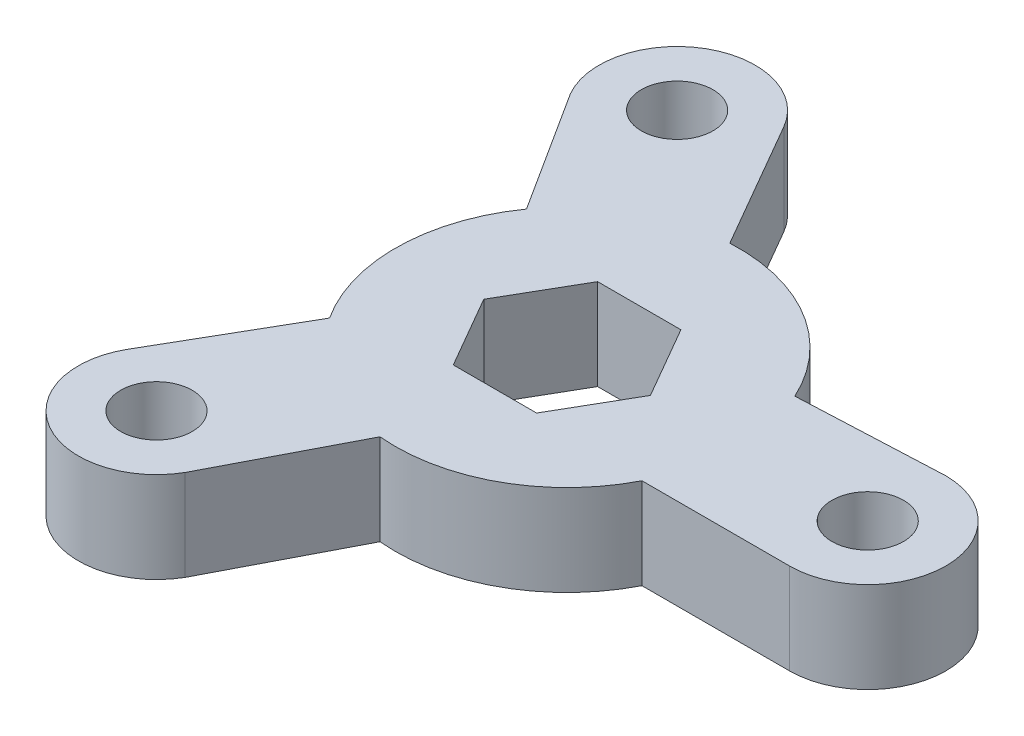
SolidWorks part; units mm, degrees
ref_plane "Front" through (0, 0, 0) normal (0, 0, 1) x (1, 0, 0)
ref_plane "Top" through (0, 0, 0) normal (0, 1, 0) x (1, 0, 0)
ref_plane "Right" through (0, 0, 0) normal (1, 0, 0) x (0, 0, -1)
sketch "Sketch1" plane through (0, 0, 0) normal (0, 1, 0) x (1, 0, 0)
  line L0 (2.5148, 0.2447) -> (13.0148, 0.2447)
  line L1 (2.5148, 0.2447) -> (-2.7352, 9.338)
  line L2 (2.5148, 0.2447) -> (-2.7352, -8.8486)
  line L3 (2.5148, 0.2447) -> (-2.7352, 9.338) construction
  line L10 (2.5148, 0.2447) -> (13.0148, 0.2447) construction
  line L11 (13.0148, -2.4841) -> (7.8583, -2.4841)
  line L12 (13.0148, 2.9736) -> (7.9691, 2.7447)
  line L13 (-5.0985, -7.4841) -> (-2.5203, -3.0185)
  line L14 (-0.372, -10.213) -> (1.9526, -5.7289)
  line L15 (-0.372, 10.7024) -> (2.2062, 6.2368)
  line L16 (-5.0985, 7.9736) -> (-2.3775, 3.7183)
  line L18 (5.4246, 0.2447) -> (3.9697, 2.7647)
  line L19 (3.9697, 2.7647) -> (1.0598, 2.7647)
  line L20 (1.0598, 2.7647) -> (-0.3951, 0.2447)
  line L21 (-0.3951, 0.2447) -> (1.0598, -2.2753)
  line L22 (1.0598, -2.2753) -> (3.9697, -2.2753)
  line L23 (3.9697, -2.2753) -> (5.4246, 0.2447)
  circle A0 centre (-2.7352, 9.338) radius 1.25
  circle A1 centre (13.0148, 0.2447) radius 1.25
  circle A2 centre (-2.7352, -8.8486) radius 1.25
  circle A3 centre (2.5148, 0.2447) radius 2.52 construction
  arc A4 (-0.372, 10.7024) -> (-5.0985, 7.9736) centre (-2.7352, 9.338) ccw
  circle A5 centre (2.5148, 0.2447) radius 6
  arc A6 (13.0148, -2.4841) -> (13.0148, 2.9736) centre (13.0148, 0.2447) ccw
  arc A7 (-5.0985, -7.4841) -> (-0.372, -10.213) centre (-2.7352, -8.8486) ccw
  point P39 (2.5148, 0.2447)
  dimension "D1" = 3
  dimension "D3" = 3
extrude "Boss-Extrude1" add sketch "Sketch1" along normal blind 3.175
